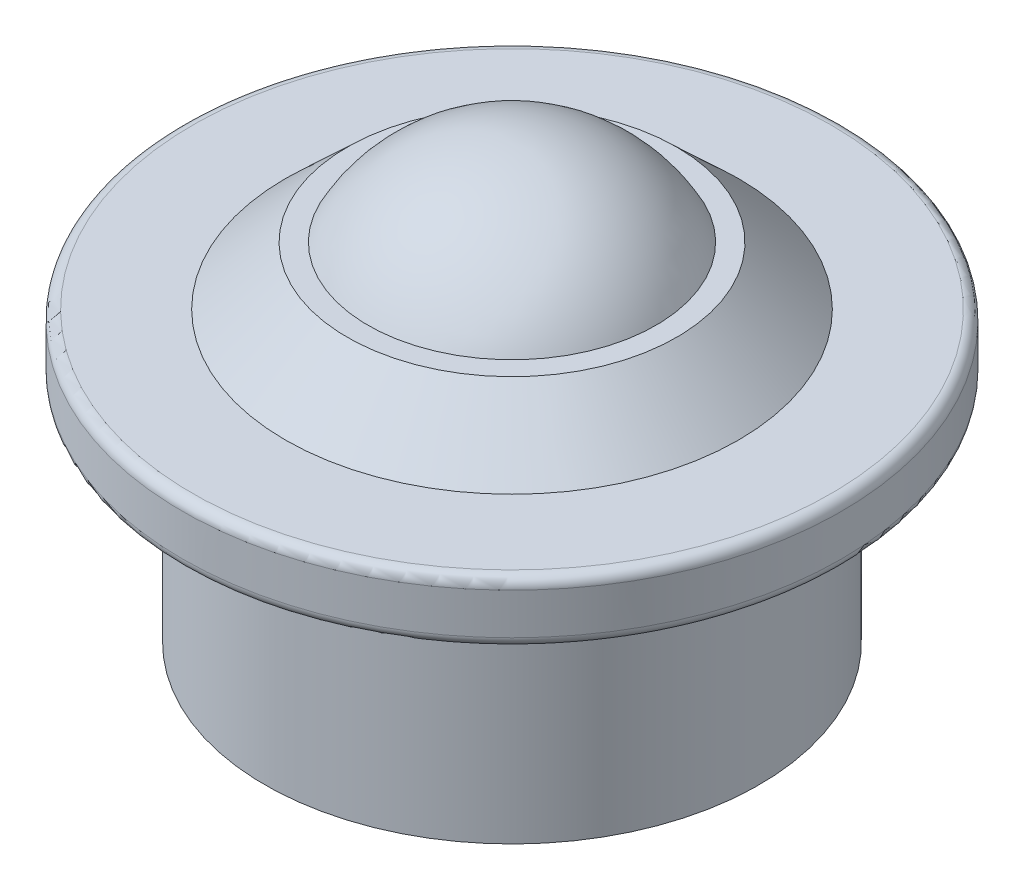
SolidWorks part; units mm, degrees
ref_plane "Plan de face" through (0, 0, 0) normal (0, 0, 1) x (1, 0, 0)
ref_plane "Plan de dessus" through (0, 0, 0) normal (0, 1, 0) x (1, 0, 0)
ref_plane "Plan de droite" through (0, 0, 0) normal (1, 0, 0) x (0, 0, -1)
sketch "Esquisse1" plane through (0, 0, 0) normal (0, 0, 1) x (1, 0, 0)
  line L0 (0, 0) -> (0, 39.602) construction
  line L1 (0, 0) -> (-12, 0)
  line L2 (-12, 0) -> (-12, 11)
  line L3 (-12, 11) -> (-16, 11)
  line L4 (-16, 11) -> (-16, 14)
  line L5 (-16, 14) -> (-11, 14)
  line L6 (-7.2051, 21) -> (5.3496, 21) construction
  line L7 (0, 21) -> (0, 13.06) construction
  line L8 (-8, 16.8215) -> (0, 16.8215) construction
  line L9 (-11, 14) -> (-8, 16.8215)
  line L10 (-8, 16.8215) -> (-6.9925, 16.8215)
  line L11 (0, 0) -> (0, 21)
  arc A0 (0, 21) -> (-6.9925, 16.8215) centre (0, 13.06) ccw
  point P12 (0, 5.12)
  dimension "D1" = 12
  dimension "D2" = 11
  dimension "D3" = 4
  dimension "D4" = 3
  dimension "D5" = 5
  dimension "D6" = 21
  dimension "D7" = 7.94
  dimension "D8" = 15.88
  dimension "D9" = 8
revolve "Révolution1" add sketch "Esquisse1" angle 360 about L11
fillet "Congé1" radius 0.5 2 edges at (0, 14, -16) (0, 11, -16)
